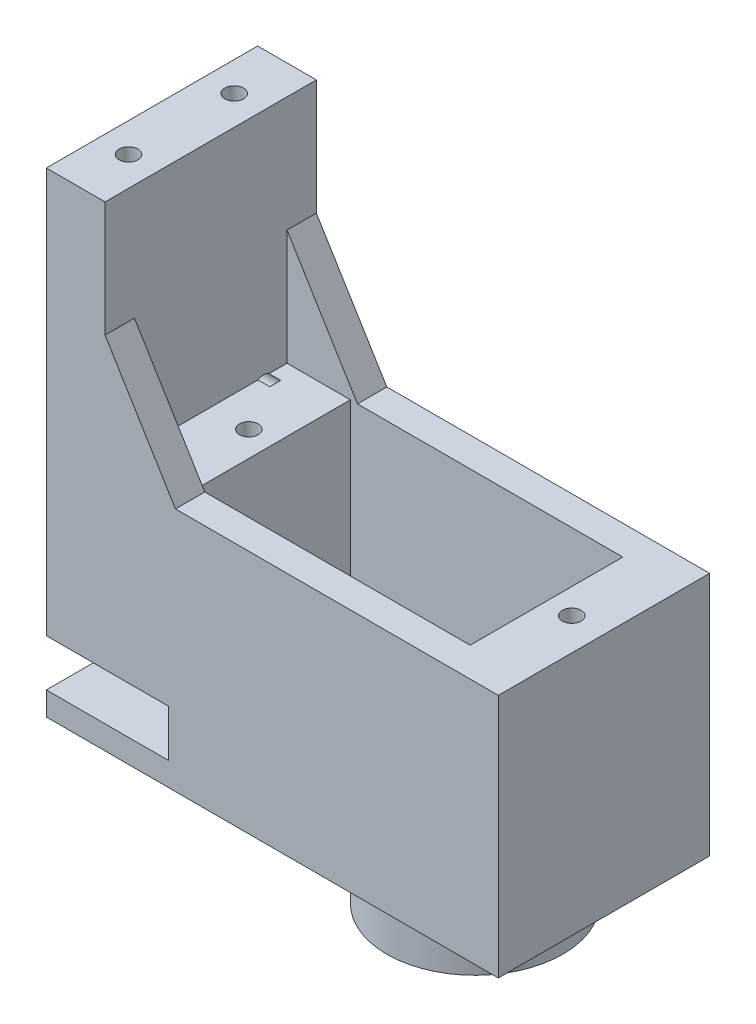
SolidWorks part; units mm, degrees
material "ABS"
ref_plane "Front Plane" through (0, 0, 0) normal (0, 0, 1) x (1, 0, 0)
ref_plane "Top Plane" through (0, 0, 0) normal (0, 1, 0) x (1, 0, 0)
ref_plane "Right Plane" through (0, 0, 0) normal (1, 0, 0) x (0, 0, -1)
sketch "Sketch1" plane through (0, 0, 0) normal (0, 0, 1) x (1, 0, 0)
  line L1 (-22, -15.7) -> (16.5, -15.7)
  line L2 (-22, -15.7) -> (-22, 5.15)
  line L3 (-22, 5.15) -> (16.5, 5.15)
  line L4 (16.5, -15.7) -> (16.5, 5.15)
extrude "Boss-Extrude1" add sketch "Sketch1" along normal mid plane 18
sketch "Sketch2" plane through (0, 0, 0) normal (0, 0, 1) x (1, 0, 0)
  line L1 (-22, 5.15) -> (-17, 5.15)
  line L2 (-22, 5.15) -> (-22, 24.8)
  line L3 (-22, 24.8) -> (-17, 24.8)
  line L4 (-17, 5.15) -> (-17, 24.8)
extrude "Boss-Extrude2" add sketch "Sketch2" along normal mid plane 18
ref_plane "Y-20_20" through (0, -20.2, 0) normal (0, 1, 0) x (1, 0, 0)
sketch "Sketch3" plane through (0, -20.2, 0) normal (0, 1, 0) x (1, 0, 0)
  circle A0 centre (5.5, 0) radius 7.5
extrude "Boss-Extrude3" add sketch "Sketch3" along normal blind 4.5
ref_plane "Y+5_15" through (0, 5.15, 0) normal (0, 1, 0) x (1, 0, 0)
sketch "Sketch4" plane through (0, 5.15, 0) normal (0, 1, 0) x (1, 0, 0)
  line L1 (-11.6, -6.5) -> (11.6, -6.5)
  line L2 (-11.6, -6.5) -> (-11.6, 6.5)
  line L3 (-11.6, 6.5) -> (11.6, 6.5)
  line L4 (11.6, -6.5) -> (11.6, 6.5)
extrude "Cut-Extrude1" cut sketch "Sketch4" against normal blind 18.85
sketch "Sketch5" plane through (0, -20.2, 0) normal (0, 1, 0) x (1, 0, 0)
  circle A0 centre (5.5, 0) radius 5
extrude "Cut-Extrude3" cut sketch "Sketch5" along normal blind 4
ref_plane "Y-13_70" through (0, -13.7, 0) normal (0, 1, 0) x (1, 0, 0)
sketch "Sketch6" plane through (0, -13.7, 0) normal (0, 1, 0) x (1, 0, 0)
  line L1 (11.6, -6.5) -> (13, -6.5)
  line L2 (11.6, -6.5) -> (11.6, 6.5)
  line L3 (11.6, 6.5) -> (13, 6.5)
  line L4 (13, -6.5) -> (13, 6.5)
extrude "Cut-Extrude5" cut sketch "Sketch6" along normal blind 5.8
sketch "Sketch7" plane through (0, 0, 0) normal (0, 0, 1) x (1, 0, 0)
  line L0 (9.9, -13.7) -> (-9.9, -13.7) construction
  line L1 (-22, -13.7) -> (-11.6, -13.7)
  line L2 (-22, -13.7) -> (-22, -9.7)
  line L3 (-22, -9.7) -> (-11.6, -9.7)
  line L4 (-11.6, -13.7) -> (-11.6, -9.7)
extrude "Cut-Extrude6" cut sketch "Sketch7" against normal through all and the other way through all
sketch "Sketch8" plane through (0, 5.15, 0) normal (0, 1, 0) x (1, 0, 0)
  circle A0 centre (-13.75, 0) radius 0.8
extrude "Cut-Extrude7" cut sketch "Sketch8" against normal blind 8
sketch "Sketch9" plane through (0, 5.15, 0) normal (0, 1, 0) x (1, 0, 0)
  circle A0 centre (13.75, 0) radius 0.8
extrude "Cut-Extrude8" cut sketch "Sketch9" against normal blind 8
ref_plane "Y+24_80" through (0, 24.8, 0) normal (0, 1, 0) x (1, 0, 0)
sketch "Sketch10" plane through (0, 24.8, 0) normal (0, 1, 0) x (1, 0, 0)
  circle A0 centre (-19.5, -4.5) radius 0.8
extrude "Cut-Extrude9" cut sketch "Sketch10" against normal blind 10
sketch "Sketch11" plane through (0, 24.8, 0) normal (0, 1, 0) x (1, 0, 0)
  circle A0 centre (-19.5, 4.5) radius 0.8
extrude "Cut-Extrude10" cut sketch "Sketch11" against normal blind 10
sketch "Sketch12" plane through (0, 0, 0) normal (0, 0, 1) x (1, 0, 0)
  line L0 (-17, 5.15) -> (-11, 5.15)
  line L1 (9.9, 5.15) -> (-9.9, 5.15) construction
  line L2 (-11, 5.15) -> (-17, 14.975)
  line L3 (-17, 5.15) -> (-17, 24.8) construction
  line L4 (-17, 14.975) -> (-17, 5.15)
extrude "Boss-Extrude4" add sketch "Sketch12" along normal mid plane 18
ref_plane "Y+15_00" through (0, 15, 0) normal (0, 1, 0) x (1, 0, 0)
sketch "Sketch13" plane through (0, 15, 0) normal (0, 1, 0) x (1, 0, 0)
  line L0 (-17, -9) -> (-17, 9) construction
  line L1 (-17, -6.5) -> (-11, -6.5)
  line L2 (-17, -6.5) -> (-17, 6.5)
  line L3 (-17, 6.5) -> (-11, 6.5)
  line L4 (-11, -6.5) -> (-11, 6.5)
extrude "Cut-Extrude11" cut sketch "Sketch13" against normal blind 9.85
ref_plane "X_LINK" through (-22, 0, 0) normal (1, 0, 0) x (0, 0, -1)
sketch "Sketch14" plane through (-22, 0, 0) normal (1, 0, 0) x (0, 0, -1)
  circle A0 centre (-4.5, -4.5) radius 0.8
  circle A1 centre (4.5, -4.5) radius 0.8
  circle A2 centre (-4.5, 4.5) radius 0.8
  circle A3 centre (4.5, 4.5) radius 0.8
extrude "Cut-Extrude13" cut sketch "Sketch14" along normal blind 6
